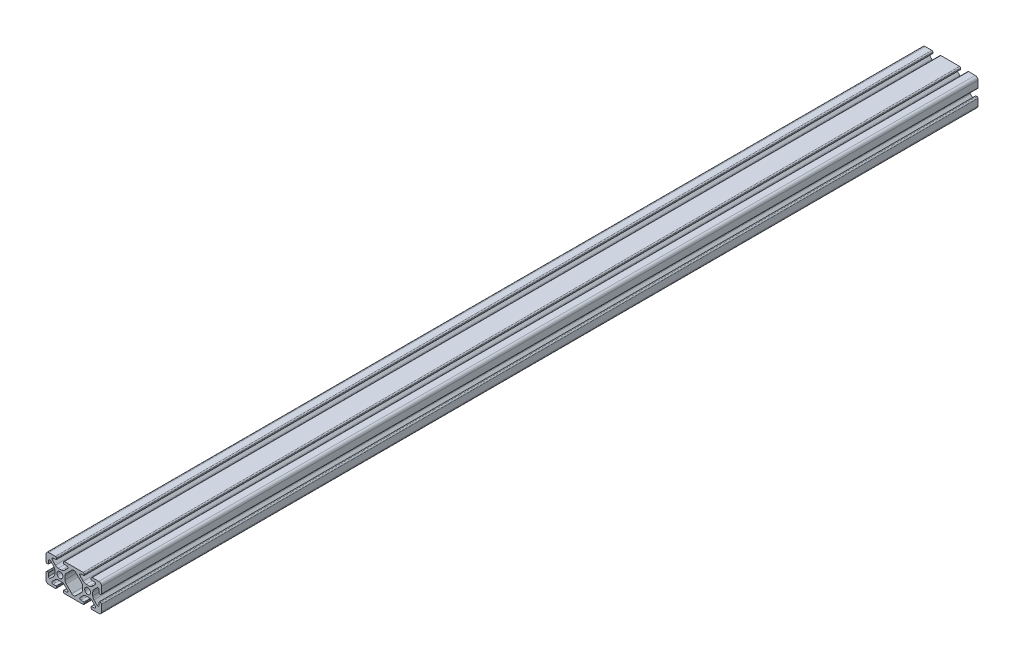
SolidWorks part; units mm, degrees
ref_plane "Plan de face" through (0, 0, 0) normal (0, 0, 1) x (1, 0, 0)
ref_plane "Plan de dessus" through (0, 0, 0) normal (0, 1, 0) x (1, 0, 0)
ref_plane "Plan de droite" through (0, 0, 0) normal (1, 0, 0) x (0, 0, -1)
ref_plane "Plan1" through (0, 0, 0) normal (0, 0, -1) x (-1, 0, 0)
sketch "Esquisse1" plane through (0, 0, 0) normal (0, 0, -1) x (-1, 0, 0)
  line L0 (-40, 6.7) -> (-40, 2)
  line L1 (-38, 0) -> (-33.3, 0)
  line L2 (-32.5, 0.8) -> (-32.5, 1.5)
  line L3 (-32.8, 1.8) -> (-34.9184, 1.8)
  line L4 (-35.5064, 3.2196) -> (-33.2547, 5.4713)
  line L5 (-31.1334, 6.35) -> (-28.8666, 6.35)
  line L6 (-26.7453, 5.4713) -> (-24.4936, 3.2196)
  line L7 (-25.0816, 1.8) -> (-27.2, 1.8)
  line L8 (-27.5, 1.5) -> (-27.5, 0.8)
  line L9 (-26.7, 0) -> (-13.3, 0)
  line L10 (-12.5, 0.8) -> (-12.5, 1.5)
  line L11 (-12.8, 1.8) -> (-14.9184, 1.8)
  line L12 (-15.5064, 3.2196) -> (-13.2547, 5.4713)
  line L13 (-11.1334, 6.35) -> (-8.8666, 6.35)
  line L14 (-6.7453, 5.4713) -> (-4.4936, 3.2196)
  line L15 (-5.0816, 1.8) -> (-7.2, 1.8)
  line L16 (-7.5, 1.5) -> (-7.5, 0.8)
  line L17 (-6.7, 0) -> (-2, 0)
  line L18 (0, 2) -> (0, 6.7)
  line L19 (-0.8, 7.5) -> (-1.5, 7.5)
  line L20 (-1.8, 7.2) -> (-1.8, 5.0816)
  line L21 (-3.2196, 4.4936) -> (-5.4713, 6.7453)
  line L22 (-6.35, 8.8666) -> (-6.35, 11.1334)
  line L23 (-5.4713, 13.2547) -> (-3.2196, 15.5064)
  line L24 (-1.8, 14.9184) -> (-1.8, 12.8)
  line L25 (-1.5, 12.5) -> (-0.8, 12.5)
  line L26 (0, 13.3) -> (0, 18)
  line L27 (-2, 20) -> (-6.7, 20)
  line L28 (-7.5, 19.2) -> (-7.5, 18.5)
  line L29 (-7.2, 18.2) -> (-5.0816, 18.2)
  line L30 (-4.4936, 16.7804) -> (-6.7453, 14.5287)
  line L31 (-8.8666, 13.65) -> (-11.1334, 13.65)
  line L32 (-13.2547, 14.5287) -> (-15.5064, 16.7804)
  line L33 (-14.9184, 18.2) -> (-12.8, 18.2)
  line L34 (-12.5, 18.5) -> (-12.5, 19.2)
  line L35 (-13.3, 20) -> (-26.7, 20)
  line L36 (-27.5, 19.2) -> (-27.5, 18.5)
  line L37 (-27.2, 18.2) -> (-25.0816, 18.2)
  line L38 (-24.4936, 16.7804) -> (-26.7453, 14.5287)
  line L39 (-28.8666, 13.65) -> (-31.1334, 13.65)
  line L40 (-33.2547, 14.5287) -> (-35.5064, 16.7804)
  line L41 (-34.9184, 18.2) -> (-32.8, 18.2)
  line L42 (-32.5, 18.5) -> (-32.5, 19.2)
  line L43 (-33.3, 20) -> (-38, 20)
  line L44 (-40, 18) -> (-40, 13.3)
  line L45 (-39.2, 12.5) -> (-38.5, 12.5)
  line L46 (-38.2, 12.8) -> (-38.2, 14.9184)
  line L47 (-36.7804, 15.5064) -> (-34.5287, 13.2547)
  line L48 (-33.65, 11.1334) -> (-33.65, 8.8666)
  line L49 (-34.5287, 6.7453) -> (-36.7804, 4.4936)
  line L50 (-38.2, 5.0816) -> (-38.2, 7.2)
  line L51 (-38.5, 7.5) -> (-39.2, 7.5)
  line L52 (-18.5858, 17.313) -> (-14.5287, 13.2559)
  line L53 (-13.65, 11.1346) -> (-13.65, 8.8654)
  line L54 (-14.5287, 6.7441) -> (-18.5858, 2.687)
  line L55 (-21.4142, 2.687) -> (-25.4713, 6.7441)
  line L56 (-26.35, 8.8654) -> (-26.35, 11.1346)
  line L57 (-25.4713, 13.2559) -> (-21.4142, 17.313)
  arc A0 (-39.2, 7.5) -> (-40, 6.7) centre (-39.2, 6.7) ccw
  arc A1 (-40, 2) -> (-38, 0) centre (-38, 2) ccw
  arc A2 (-33.3, 0) -> (-32.5, 0.8) centre (-33.3, 0.8) ccw
  arc A3 (-32.5, 1.5) -> (-32.8, 1.8) centre (-32.8, 1.5) ccw
  arc A4 (-34.9184, 1.8) -> (-35.5064, 3.2196) centre (-34.9184, 2.6316) cw
  arc A5 (-33.2547, 5.4713) -> (-31.1334, 6.35) centre (-31.1334, 3.35) cw
  arc A6 (-28.8666, 6.35) -> (-26.7453, 5.4713) centre (-28.8666, 3.35) cw
  arc A7 (-24.4936, 3.2196) -> (-25.0816, 1.8) centre (-25.0816, 2.6316) cw
  arc A8 (-27.2, 1.8) -> (-27.5, 1.5) centre (-27.2, 1.5) ccw
  arc A9 (-27.5, 0.8) -> (-26.7, 0) centre (-26.7, 0.8) ccw
  arc A10 (-13.3, 0) -> (-12.5, 0.8) centre (-13.3, 0.8) ccw
  arc A11 (-12.5, 1.5) -> (-12.8, 1.8) centre (-12.8, 1.5) ccw
  arc A12 (-14.9184, 1.8) -> (-15.5064, 3.2196) centre (-14.9184, 2.6316) cw
  arc A13 (-13.2547, 5.4713) -> (-11.1334, 6.35) centre (-11.1334, 3.35) cw
  arc A14 (-8.8666, 6.35) -> (-6.7453, 5.4713) centre (-8.8666, 3.35) cw
  arc A15 (-4.4936, 3.2196) -> (-5.0816, 1.8) centre (-5.0816, 2.6316) cw
  arc A16 (-7.2, 1.8) -> (-7.5, 1.5) centre (-7.2, 1.5) ccw
  arc A17 (-7.5, 0.8) -> (-6.7, 0) centre (-6.7, 0.8) ccw
  arc A18 (-2, 0) -> (0, 2) centre (-2, 2) ccw
  arc A19 (0, 6.7) -> (-0.8, 7.5) centre (-0.8, 6.7) ccw
  arc A20 (-1.5, 7.5) -> (-1.8, 7.2) centre (-1.5, 7.2) ccw
  arc A21 (-1.8, 5.0816) -> (-3.2196, 4.4936) centre (-2.6316, 5.0816) cw
  arc A22 (-5.4713, 6.7453) -> (-6.35, 8.8666) centre (-3.35, 8.8666) cw
  arc A23 (-6.35, 11.1334) -> (-5.4713, 13.2547) centre (-3.35, 11.1334) cw
  arc A24 (-3.2196, 15.5064) -> (-1.8, 14.9184) centre (-2.6316, 14.9184) cw
  arc A25 (-1.8, 12.8) -> (-1.5, 12.5) centre (-1.5, 12.8) ccw
  arc A26 (-0.8, 12.5) -> (0, 13.3) centre (-0.8, 13.3) ccw
  arc A27 (0, 18) -> (-2, 20) centre (-2, 18) ccw
  arc A28 (-6.7, 20) -> (-7.5, 19.2) centre (-6.7, 19.2) ccw
  arc A29 (-7.5, 18.5) -> (-7.2, 18.2) centre (-7.2, 18.5) ccw
  arc A30 (-5.0816, 18.2) -> (-4.4936, 16.7804) centre (-5.0816, 17.3684) cw
  arc A31 (-6.7453, 14.5287) -> (-8.8666, 13.65) centre (-8.8666, 16.65) cw
  arc A32 (-11.1334, 13.65) -> (-13.2547, 14.5287) centre (-11.1334, 16.65) cw
  arc A33 (-15.5064, 16.7804) -> (-14.9184, 18.2) centre (-14.9184, 17.3684) cw
  arc A34 (-12.8, 18.2) -> (-12.5, 18.5) centre (-12.8, 18.5) ccw
  arc A35 (-12.5, 19.2) -> (-13.3, 20) centre (-13.3, 19.2) ccw
  arc A36 (-26.7, 20) -> (-27.5, 19.2) centre (-26.7, 19.2) ccw
  arc A37 (-27.5, 18.5) -> (-27.2, 18.2) centre (-27.2, 18.5) ccw
  arc A38 (-25.0816, 18.2) -> (-24.4936, 16.7804) centre (-25.0816, 17.3684) cw
  arc A39 (-26.7453, 14.5287) -> (-28.8666, 13.65) centre (-28.8666, 16.65) cw
  arc A40 (-31.1334, 13.65) -> (-33.2547, 14.5287) centre (-31.1334, 16.65) cw
  arc A41 (-35.5064, 16.7804) -> (-34.9184, 18.2) centre (-34.9184, 17.3684) cw
  arc A42 (-32.8, 18.2) -> (-32.5, 18.5) centre (-32.8, 18.5) ccw
  arc A43 (-32.5, 19.2) -> (-33.3, 20) centre (-33.3, 19.2) ccw
  arc A44 (-38, 20) -> (-40, 18) centre (-38, 18) ccw
  arc A45 (-40, 13.3) -> (-39.2, 12.5) centre (-39.2, 13.3) ccw
  arc A46 (-38.5, 12.5) -> (-38.2, 12.8) centre (-38.5, 12.8) ccw
  arc A47 (-38.2, 14.9184) -> (-36.7804, 15.5064) centre (-37.3684, 14.9184) cw
  arc A48 (-34.5287, 13.2547) -> (-33.65, 11.1334) centre (-36.65, 11.1334) cw
  arc A49 (-33.65, 8.8666) -> (-34.5287, 6.7453) centre (-36.65, 8.8666) cw
  arc A50 (-36.7804, 4.4936) -> (-38.2, 5.0816) centre (-37.3684, 5.0816) cw
  arc A51 (-38.2, 7.2) -> (-38.5, 7.5) centre (-38.5, 7.2) ccw
  circle A52 centre (-10, 10) radius 2.15
  circle A53 centre (-30, 10) radius 2.15
  arc A54 (-21.4142, 17.313) -> (-18.5858, 17.313) centre (-20, 15.8988) cw
  arc A55 (-14.5287, 13.2559) -> (-13.65, 11.1346) centre (-16.65, 11.1346) cw
  arc A56 (-13.65, 8.8654) -> (-14.5287, 6.7441) centre (-16.65, 8.8654) cw
  arc A57 (-18.5858, 2.687) -> (-21.4142, 2.687) centre (-20, 4.1012) cw
  arc A58 (-25.4713, 6.7441) -> (-26.35, 8.8654) centre (-23.35, 8.8654) cw
  arc A59 (-26.35, 11.1346) -> (-25.4713, 13.2559) centre (-23.35, 11.1346) cw
extrude "Boss.-Extru.1" add sketch "Esquisse1" against normal mid plane 631
